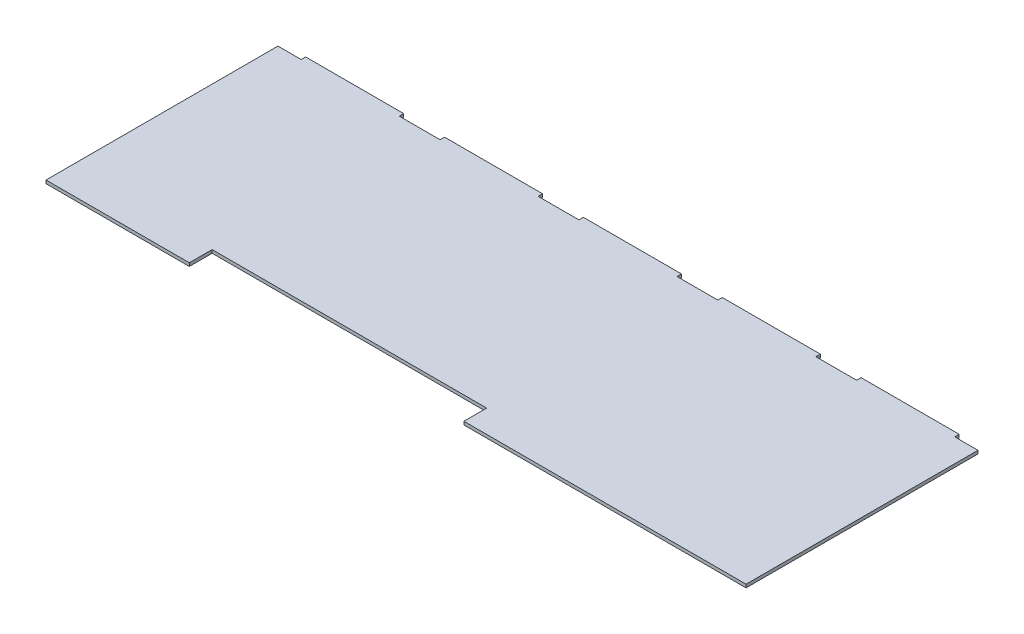
SolidWorks part; units mm, degrees
material "6061-T6 (SS)"
ref_plane "X-Y Datum" through (0, 0, 0) normal (0, 0, 1) x (1, 0, 0)
ref_plane "X-Z Datum" through (0, 0, 0) normal (0, 1, 0) x (1, 0, 0)
ref_plane "Y-Z Datum" through (0, 0, 0) normal (1, 0, 0) x (0, 0, -1)
sketch "Sketch1" plane through (0, 0, 0) normal (0, 1, 0) x (1, 0, 0)
  line L1 (-249.174, 82.55) -> (249.174, 82.55)
  line L2 (-249.174, 82.55) -> (-249.174, -82.55)
  line L3 (-249.174, -82.55) -> (249.174, -82.55)
  line L4 (249.174, 82.55) -> (249.174, -82.55)
  line L5 (-249.174, 82.55) -> (249.174, -82.55) construction
  line L6 (-249.174, -82.55) -> (249.174, 82.55) construction
  point P0 (0, 0)
  dimension "D1" = 498.348
  dimension "D2" = 165.1
extrude "Boss-Extrude1" add sketch "Sketch1" along normal mid plane 2.286
sketch "Sketch2" plane through (0, 0, -82.55) normal (0, 0, -1) x (-1, 0, 0)
  line L24 (-232.6386, -1.143) -> (-232.6386, 1.143)
  line L25 (-232.6386, 1.143) -> (-162.7886, 1.143)
  line L26 (-162.7886, -1.143) -> (-232.6386, -1.143)
  line L27 (-162.7886, 1.143) -> (-162.7886, -1.143)
extrude "Boss-Extrude2" add sketch "Sketch2" along normal blind 3.175
pattern_linear "LPattern1" count 5 spacing 98.8568 along (-1, 0, 0) of "Boss-Extrude2"
sketch "Sketch3" plane through (0, -1.143, 0) normal (0, -1, 0) x (1, 0, 0)
  line L0 (-147.1422, 82.55) -> (-147.1422, -82.55) construction
  line L1 (-50.5714, 184.15) -> (-50.5714, -82.55) construction
  line L2 (-147.1422, 82.55) -> (-147.1422, -82.55)
  line L3 (-50.5714, 184.15) -> (-50.5714, -82.55)
  line L4 (-135.9408, 66.3102) -> (-57.4548, 66.3102) construction
  line L5 (-147.1422, 66.3102) -> (-50.5714, 66.3102)
  line L7 (-49.4284, 184.15) -> (-49.4284, -82.55) construction
  line L8 (48.2854, 82.55) -> (48.2854, -82.55)
  line L9 (48.2854, 66.3102) -> (-48.2854, 66.3102)
  line L10 (-48.2854, 184.15) -> (-48.2854, -82.55)
  line L11 (-50.5714, 66.3102) -> (-48.2854, 66.3102)
  line M2 (249.174, 82.55) -> (-249.174, 82.55)
  dimension "D1" = 1.143
extrude "Cut-Extrude1" cut sketch "Sketch3" against normal through all contours L2 L5 L3 M2 | L7 L11 L10 M2 | L7 L3 L11 M2 | L10 L9 L8 M2
